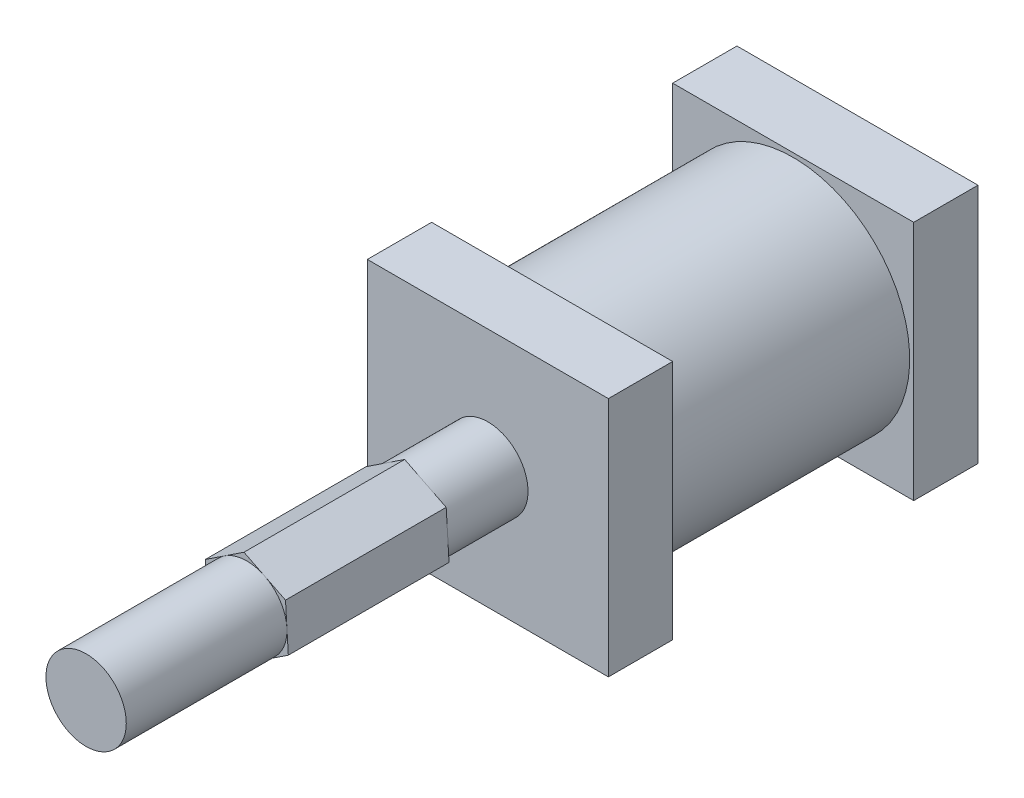
SolidWorks part; units mm, degrees
ref_plane "Front Plane" through (0, 0, 0) normal (0, 0, 1) x (1, 0, 0)
ref_plane "Top Plane" through (0, 0, 0) normal (0, 1, 0) x (1, 0, 0)
ref_plane "Right Plane" through (0, 0, 0) normal (1, 0, 0) x (0, 0, -1)
sketch "Sketch1" plane through (0, 0, 0) normal (0, 0, 1) x (1, 0, 0)
  line L1 (0, 0) -> (38.1, 0)
  line L2 (0, 0) -> (0, 38.1)
  line L3 (0, 38.1) -> (38.1, 38.1)
  line L4 (38.1, 0) -> (38.1, 38.1)
  dimension "D1" = 38.1
  dimension "D2" = 38.1
extrude "Boss-Extrude1" add sketch "Sketch1" along normal blind 10.16
sketch "Sketch2" plane through (0, 0, 10.16) normal (0, 0, 1) x (1, 0, 0)
  line L0 (0, 38.1) -> (0, 0) construction
  line L1 (38.1, 38.1) -> (0, 38.1) construction
  circle A0 centre (19.05, 19.05) radius 18.415
  dimension "D3" = 36.83
  dimension "D1" = 19.05
  dimension "D2" = 19.05
extrude "Boss-Extrude2" add sketch "Sketch2" along normal blind 38.1
sketch "Sketch3" plane through (0, 0, 48.26) normal (0, 0, 1) x (1, 0, 0)
  line L1 (0, 0) -> (38.1, 0)
  line L2 (0, 0) -> (0, 38.1)
  line L3 (0, 38.1) -> (38.1, 38.1)
  line L4 (38.1, 0) -> (38.1, 38.1)
extrude "Boss-Extrude3" add sketch "Sketch3" along normal blind 10.16
sketch "Sketch4" plane through (0, 0, 58.42) normal (0, 0, 1) x (1, 0, 0)
  line L0 (38.1, 0) -> (38.1, 38.1) construction
  line L1 (0, 0) -> (38.1, 0) construction
  circle A0 centre (19.05, 19.05) radius 6.35
  dimension "D1" = 12.7
  dimension "D2" = 19.05
  dimension "D3" = 19.05
extrude "Boss-Extrude4" add sketch "Sketch4" along normal blind 12.7
sketch "Sketch5" plane through (0, 0, 71.12) normal (0, 0, 1) x (1, 0, 0)
  line L1 (25.1641, 23.0974) -> (18.6019, 26.3686)
  line L2 (18.6019, 26.3686) -> (12.4878, 22.3213)
  line L3 (12.4878, 22.3213) -> (12.9359, 15.0026)
  line L4 (12.9359, 15.0026) -> (19.4981, 11.7314)
  line L5 (19.4981, 11.7314) -> (25.6122, 15.7787)
  line L6 (25.6122, 15.7787) -> (25.1641, 23.0974)
  circle A0 centre (19.05, 19.05) radius 6.35 construction
extrude "Boss-Extrude5" add sketch "Sketch5" along normal blind 25.4
sketch "Sketch6" plane through (0, 0, 96.52) normal (0, 0, 1) x (1, 0, 0)
  line L0 (0, 38.1) -> (0, 0) construction
  line L1 (0, 0) -> (38.1, 0) construction
  circle A0 centre (19.05, 19.05) radius 6.35
  dimension "D1" = 12.7
  dimension "D2" = 19.05
  dimension "D3" = 19.05
extrude "Boss-Extrude6" add sketch "Sketch6" along normal blind 25.4
